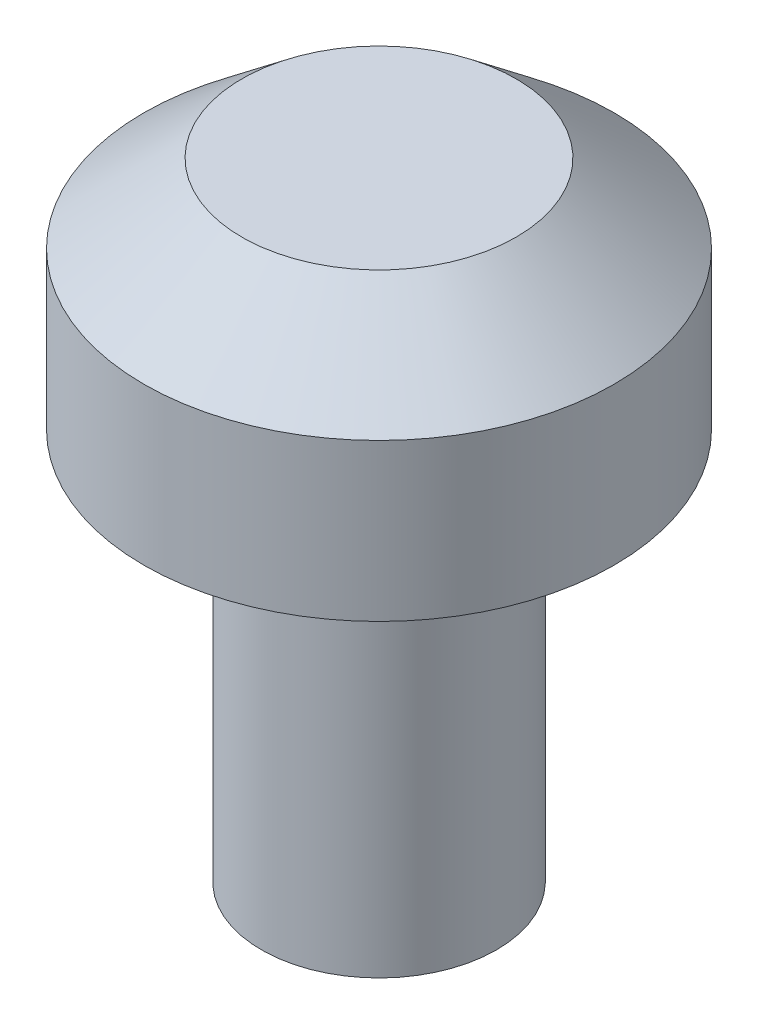
SolidWorks part; units mm, degrees
ref_plane "Alzado" through (0, 0, 0) normal (0, 0, 1) x (1, 0, 0)
ref_plane "Planta" through (0, 0, 0) normal (0, 1, 0) x (1, 0, 0)
ref_plane "Vista lateral" through (0, 0, 0) normal (1, 0, 0) x (0, 0, -1)
sketch "Croquis3" plane through (0, 0, 0) normal (0, 0, 1) x (1, 0, 0)
  line L0 (0, 0) -> (-1.5, 0)
  line L1 (-1.5, 0) -> (-1.5, 5)
  line L2 (-1.5, 5) -> (-3, 5)
  line L3 (-3, 5) -> (-3, 7)
  line L4 (-3, 7) -> (-1.75, 8)
  line L5 (-1.75, 8) -> (0, 8)
  line L6 (0, 8) -> (0, 0) construction
  line L7 (0, 0) -> (0, 8) construction
  line L8 (0, 0) -> (0, 8)
  line L9 (0, 8) -> (0, 0)
  point P4 (-0.875, 8)
  dimension "D1" = 5
  dimension "D2" = 3
  dimension "D3" = 6
  dimension "D4" = 3
  dimension "D5" = 2
  dimension "D6" = 3.5
revolve "Revolución1" add sketch "Croquis3" angle 360 about L8
